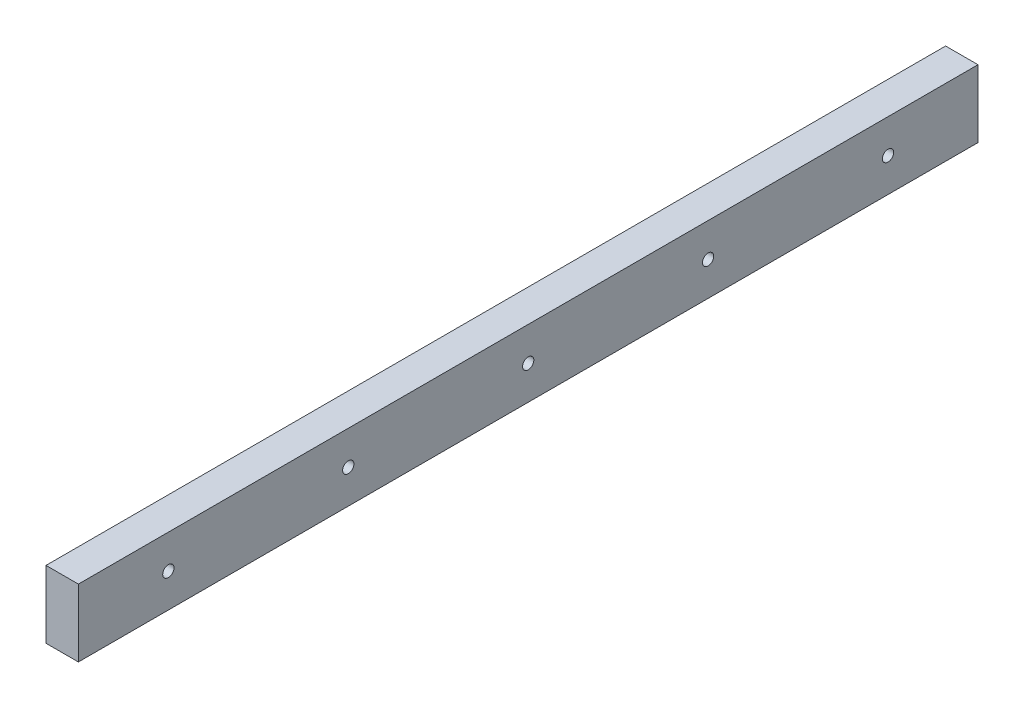
SolidWorks part; units mm, degrees
ref_plane "Front" through (0, 0, 0) normal (0, 0, 1) x (1, 0, 0)
ref_plane "Top" through (0, 0, 0) normal (0, 1, 0) x (1, 0, 0)
ref_plane "Right" through (0, 0, 0) normal (1, 0, 0) x (0, 0, -1)
sketch "Sketch1" plane through (0, 0, 0) normal (1, 0, 0) x (0, 0, -1)
  line L1 (254, -19.05) -> (-254, -19.05)
  line L2 (254, -19.05) -> (254, 19.05)
  line L3 (254, 19.05) -> (-254, 19.05)
  line L4 (-254, -19.05) -> (-254, 19.05)
  line L5 (254, -19.05) -> (-254, 19.05) construction
  line L6 (254, 19.05) -> (-254, -19.05) construction
  point P0 (0, 0)
  dimension "D1" = 38.1
  dimension "D2" = 508
extrude "Boss-Extrude1" add sketch "Sketch1" along normal blind 18.288
sketch "Sketch2" plane through (18.288, 0, 0) normal (1, 0, 0) x (0, 0, -1)
  line L0 (254, -19.05) -> (254, 19.05) construction
  circle A0 centre (203.2, 0) radius 3.175
  circle A1 centre (101.6, 0) radius 3.175
  circle A2 centre (0, 0) radius 3.175
  circle A3 centre (-101.6, 0) radius 3.175
  circle A4 centre (-203.2, 0) radius 3.175
  dimension "D1" = 6.35
  dimension "D2" = 50.8
  dimension "D3" = 5
extrude "Cut-Extrude1" cut sketch "Sketch2" against normal through all
